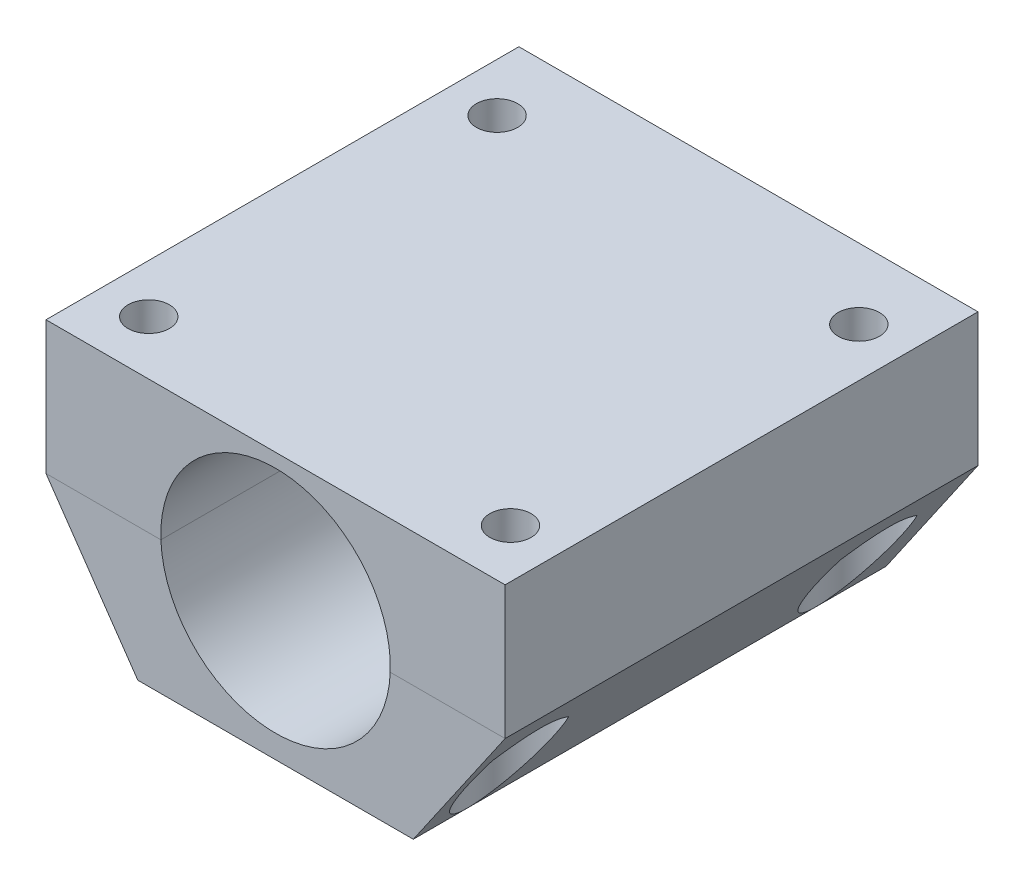
SolidWorks part; units mm, degrees
ref_plane "Plan de face" through (0, 0, 0) normal (0, 0, 1) x (1, 0, 0)
ref_plane "Plan de dessus" through (0, 0, 0) normal (0, 1, 0) x (1, 0, 0)
ref_plane "Plan de droite" through (0, 0, 0) normal (1, 0, 0) x (0, 0, -1)
sketch "Esquisse1" plane through (0, 0, 0) normal (0, 0, 1) x (1, 0, 0)
  line L4 (0, 12.5) -> (0, 14) construction
  line L5 (0, -12.5) -> (0, -15) construction
  line L7 (-15, 14) -> (15, 14)
  line L8 (15, 14) -> (15, -15)
  line L9 (15, -15) -> (-15, -15)
  line L10 (-15, -15) -> (-15, 14)
  line L11 (-15, -0.5) -> (-25, -0.5)
  line L12 (-25, -0.5) -> (-25, 14)
  line L13 (-25, 14) -> (-15, 14)
  line L14 (15, 14) -> (25, 14)
  line L15 (25, 14) -> (25, -0.5)
  line L16 (25, -0.5) -> (15, -0.5)
  line L17 (-25, -0.5) -> (-15, -15)
  line L18 (15, -15) -> (25, -0.5)
  line L19 (25, -0.5) -> (-25, -0.5) construction
  circle A0 centre (0, 0) radius 12.5
  point P9 (0, 14)
  dimension "D1" = 25
  dimension "D2" = 30
  dimension "D3" = 1.5
  dimension "D4" = 2.5
  dimension "D5" = 10
  dimension "D6" = 10
extrude "Boss.-Extru.1" add sketch "Esquisse1" along normal blind 50 contours L13 L12 L11 L10 | L11 L17 L10 | L10 L9 L8 L7 A0 | L8 L18 L16 | L16 L15 L14 L8
ref_plane "Plan1" through (0, -0.5, 0) normal (0, 1, 0) x (1, 0, 0)
hole_wizard "Fraisage pour vis à tête fraisée M41" positions "Esquisse24" profile "Esquisse25" countersink size "M4" standard "ISO" end condition through all
sketch "Esquisse24" plane through (0, -15, 0) normal (0, -1, 0) x (-1, 0, 0)
  point P0 (-19.6987, -6.1768)
  point P2 (19.6987, -6.1768)
  point P4 (19.6987, -44.115)
  point P6 (-19.6987, -44.115)
sketch "Esquisse25" plane through (19.6987, -15, 6.1768) normal (1, 0, 0) x (0, 0, -1)
  line L0 (0, 0) -> (0, 29)
  line L1 (0, 29) -> (2.25, 29)
  line L2 (2.25, 29) -> (2.25, 12.45)
  line L3 (2.25, 12.45) -> (4.7, 10)
  line L4 (4.7, 10) -> (4.7, 0)
  line L6 (4.7, 0) -> (0, 0)
  line L7 (-2.25, 12.45) -> (-4.7, 10) construction
  line L11 (0, -6.35) -> (0, 107.95) construction
  dimension "Diamètre du perçage jusqu'au prochain" = 4.5
  dimension "Profondeur du perçage jusqu'au prochain" = 29
  dimension "Diamètre du fraisage" = 9.4
  dimension "Angle du fraisage" = 90
  dimension "Dégagement de la tête" = 10
sketch "Esquisse26" plane through (0, 0, 0) normal (0, 0, -1) x (-1, 0, 0)
  line L0 (-25, 14) -> (25, 14)
  line L1 (25, 14) -> (25, -0.5)
  line L2 (25, -0.5) -> (15, -15)
  line L3 (15, -15) -> (-15, -15)
  line L4 (-15, -15) -> (-25, -0.5)
  line L5 (-25, -0.5) -> (-25, 14)
  circle A0 centre (0, 0) radius 3.75
  dimension "D1" = 7.5
extrude "Boss.-Extru.2" add sketch "Esquisse26" along normal blind 1.5
hole_wizard "Fraisage pour vis à tête fraisée M31" positions "Esquisse27" profile "Esquisse28" countersink size "M3" standard "ISO" end condition through all
sketch "Esquisse27" plane through (0, 0, -1.5) normal (0, 0, -1) x (-1, 0, 0)
  circle A0 centre (0, 0) radius 3.75 construction
  point P0 (-8.5, 0)
  point P2 (8.5, 0)
  dimension "D1" = 8.5
  dimension "D2" = 8.5
sketch "Esquisse28" plane through (8.5, 0, -1.5) normal (1, 0, 0) x (0, 1, 0)
  line L0 (0, 0) -> (0, 51.5)
  line L1 (0, 51.5) -> (1.7, 51.5)
  line L2 (1.7, 51.5) -> (1.7, 1.45)
  line L3 (1.7, 1.45) -> (3.15, 0)
  line L5 (3.15, 0) -> (0, 0)
  line L6 (-1.7, 1.45) -> (-3.15, 0) construction
  line L11 (0, -6.35) -> (0, 107.95) construction
  dimension "Diamètre du perçage jusqu'au prochain" = 3.4
  dimension "Profondeur du perçage jusqu'au prochain" = 51.5
  dimension "Diamètre du fraisage entrant" = 6.3
  dimension "Angle du fraisage entrant" = 90
split "Fractionner1" trim tools "Plan1" bodies to split 118 resulting bodies 119 120
